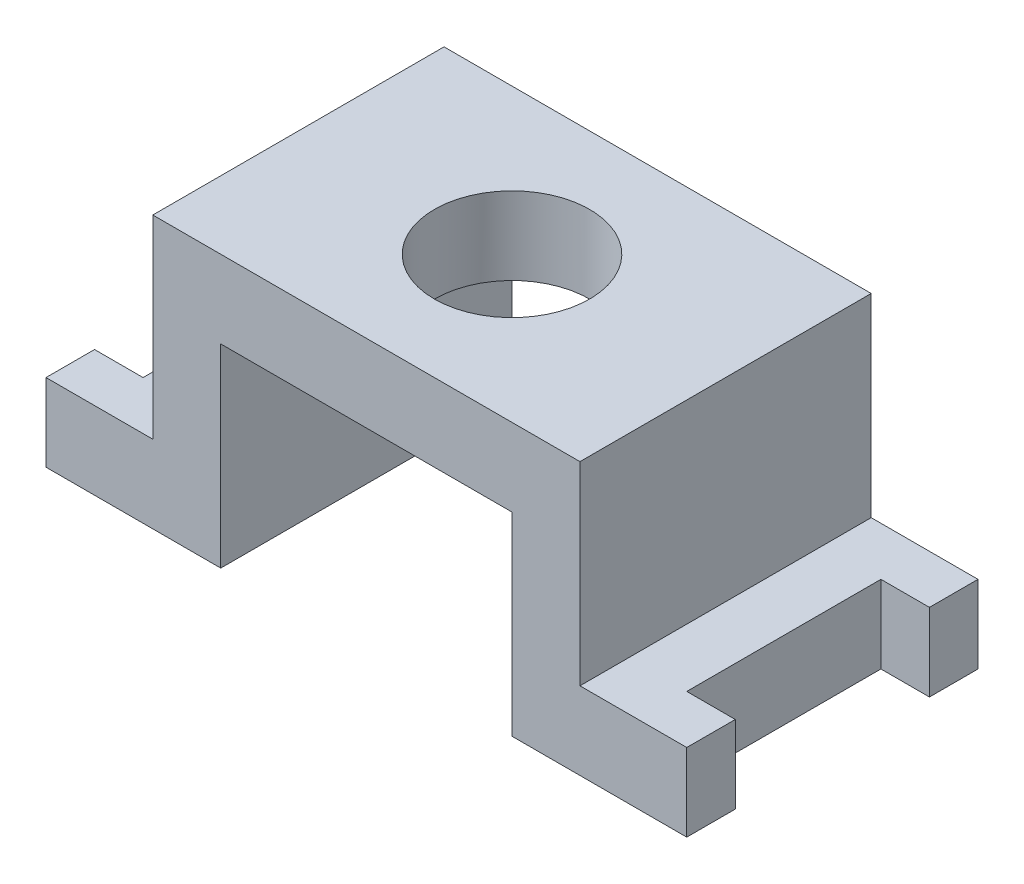
SolidWorks part; units mm, degrees
ref_plane "Спереди" through (0, 0, 0) normal (0, 0, 1) x (1, 0, 0)
ref_plane "Сверху" through (0, 0, 0) normal (0, 1, 0) x (1, 0, 0)
ref_plane "Справа" through (0, 0, 0) normal (1, 0, 0) x (0, 0, -1)
sketch "Эскиз1" plane through (0, 0, 0) normal (0, 0, 1) x (1, 0, 0)
  line L16 (0, 0) -> (0, 8)
  line L17 (0, 8) -> (11, 8)
  line L18 (11, 8) -> (11, 28)
  line L19 (11, 28) -> (55, 28)
  line L20 (55, 28) -> (55, 8)
  line L21 (55, 8) -> (66, 8)
  line L22 (66, 8) -> (66, 0)
  line L23 (66, 0) -> (48, 0)
  line L24 (48, 0) -> (48, 20)
  line L25 (48, 20) -> (18, 20)
  line L26 (18, 20) -> (18, 0)
  line L27 (18, 0) -> (0, 0)
  dimension "D1" = 8
  dimension "D2" = 28
  dimension "D3" = 8
  dimension "D4" = 44
  dimension "D5" = 11
  dimension "D6" = 11
  dimension "D7" = 18
  dimension "D8" = 18
  dimension "D9" = 20
extrude "Бобышка-Вытянуть1" add sketch "Эскиз1" along normal blind 30
sketch "Эскиз3" plane through (0, 8, 0) normal (0, 1, 0) x (1, 0, 0)
  line L0 (0, -25) -> (5, -25)
  line L1 (0, -25) -> (0, -5)
  line L2 (5, -25) -> (5, -5)
  line L3 (0, -5) -> (5, -5)
  line L4 (0, -30) -> (0, 0) construction
  line L5 (66, -25) -> (61, -25)
  line L6 (66, -25) -> (66, -5)
  line L7 (61, -25) -> (61, -5)
  line L8 (66, -5) -> (61, -5)
  line L10 (66, -30) -> (66, 0) construction
  dimension "D1" = 5
  dimension "D2" = 5
  dimension "D3" = 20
  dimension "D4" = 5
  dimension "D5" = 20
extrude "Вырез-Вытянуть1" cut sketch "Эскиз3" against normal through all
sketch "Эскиз4" plane through (0, 28, 0) normal (0, 1, 0) x (1, 0, 0)
  line L0 (55, 0) -> (11, 0) construction
  circle A0 centre (33, -15) radius 8
  point P2 (0, 0)
  dimension "D1" = 16
  dimension "D2" = 15
extrude "Вырез-Вытянуть2" cut sketch "Эскиз4" against normal through all
